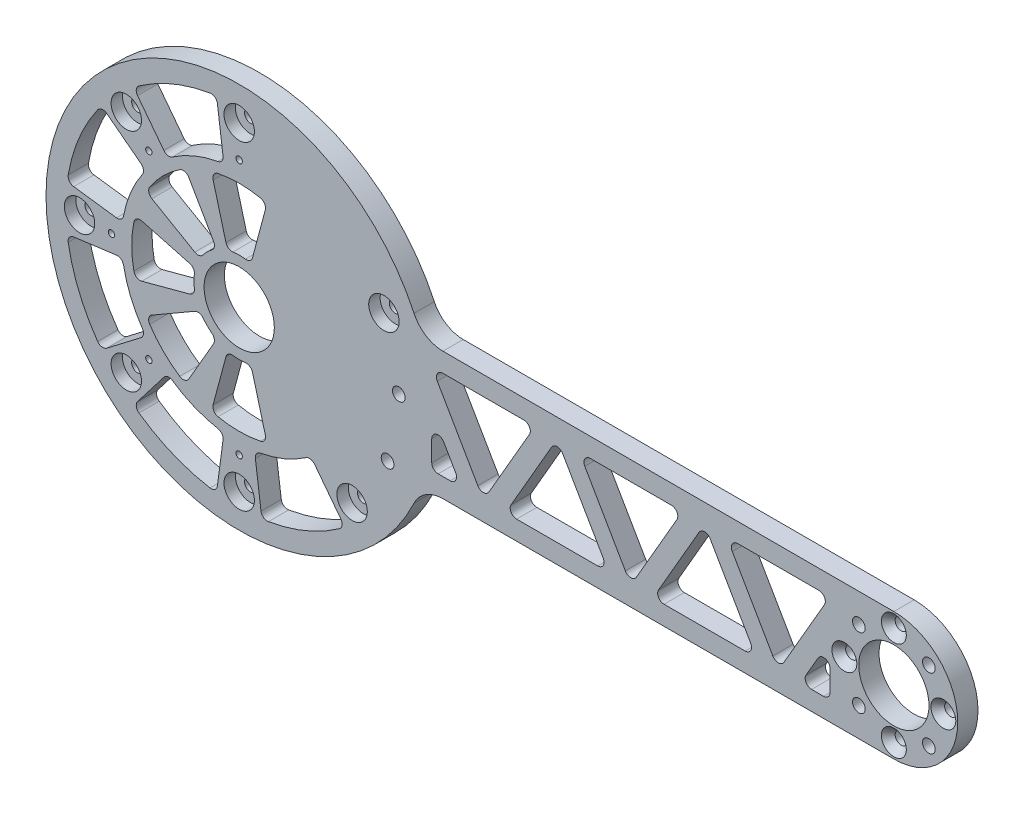
SolidWorks part; units mm, degrees
material "Balsa"
ref_plane "Front Plane" through (0, 0, 0) normal (0, 0, 1) x (1, 0, 0)
ref_plane "Top Plane" through (0, 0, 0) normal (0, 1, 0) x (1, 0, 0)
ref_plane "Right Plane" through (0, 0, 0) normal (1, 0, 0) x (0, 0, -1)
sketch "Sketch1" plane through (0, 0, 0) normal (0, 0, 1) x (1, 0, 0)
  line L0 (57.0986, -20) -> (205, -20)
  line L1 (57.0986, 20) -> (205, 20)
  line L2 (45.3154, 21.1309) -> (0, 0) construction
  line L3 (0, 0) -> (35.3553, -35.3553) construction
  line L4 (49.9788, 1.4542) -> (0, 0) construction
  line L5 (0, 0) -> (46.4674, -18.4603) construction
  arc A0 (57.0986, -20) -> (57.0986, 20) centre (0, 0) cw
  arc A1 (205, 20) -> (205, -20) centre (205, 0) cw
  circle A2 centre (0, 0) radius 60.5 construction
  circle A3 centre (0, 0) radius 11
  circle A4 centre (45.3154, 21.1309) radius 1.8986
  circle A5 centre (0, 0) radius 40 construction
  circle A6 centre (0, 0) radius 50 construction
  circle A7 centre (49.9788, 1.4542) radius 1.9939
  circle A8 centre (205, 0) radius 11
  circle A9 centre (46.4674, -18.4603) radius 1.9939
  circle A10 centre (205, 0) radius 15.5 construction
  circle A11 centre (205, -15.5) radius 1.8987
  circle A12 centre (215.9602, -10.9602) radius 1.9939
  circle A13 centre (189.5, 0) radius 1.8987
  circle A14 centre (194.0398, -10.9602) radius 1.9939
  circle A15 centre (205, 15.5) radius 1.8987
  circle A16 centre (194.0398, 10.9602) radius 1.9939
  circle A17 centre (220.5, 0) radius 1.8987
  circle A18 centre (215.9602, 10.9602) radius 1.9939
  circle A29 centre (0, -40) radius 1
  circle A30 centre (0, -50) radius 1.8986
  circle A37 centre (-28.2843, -28.2843) radius 1
  circle A38 centre (-35.3553, -35.3553) radius 1.8986
  circle A39 centre (-40, 0) radius 1
  circle A40 centre (-50, 0) radius 1.8986
  circle A41 centre (-28.2843, 28.2843) radius 1
  circle A42 centre (-35.3553, 35.3553) radius 1.8986
  circle A43 centre (0, 40) radius 1
  circle A44 centre (0, 50) radius 1.8986
  circle A45 centre (28.2843, 28.2843) radius 1 construction
  circle A46 centre (35.3553, 35.3553) radius 1.8986 construction
  circle A47 centre (40, 0) radius 1 construction
  circle A48 centre (50, 0) radius 1.8986 construction
  circle A49 centre (28.2843, -28.2843) radius 1 construction
  circle A50 centre (35.3553, -35.3553) radius 1.8986
  dimension "D1" = 121
  dimension "D4" = 22
  dimension "D6" = 100
  dimension "D7" = 80
  dimension "D8" = 70
  dimension "D9" = 3.7973
  dimension "D10" = 3.9878
  dimension "D15" = 3.7973
  dimension "D16" = 2
  dimension "D17" = 3.7973
  dimension "D18" = 3.9878
  dimension "D5" = 31
  dimension "D19" = 3.9878
  dimension "D2" = 40
  dimension "D3" = 205
  dimension "D11" = 45
  dimension "D13" = 23.333
  dimension "D14" = 23.333
  dimension "D12" = 4
  dimension "D21" = 8
extrude "Boss-Extrude1" add sketch "Sketch1" along normal blind 6.35
fillet "Fillet1" radius 10 2 edges at (57.0986, -20, 3.175) (57.0986, 20, 3.175)
sketch "Sketch2" plane through (0, 0, 6.35) normal (0, 0, 1) x (1, 0, 0)
  line L0 (60.2923, 14) -> (92.624, 14)
  line L1 (92.624, 14) -> (76.4581, -14)
  line L2 (76.4581, -14) -> (60.2923, 14)
  line L3 (83.3864, -14) -> (99.5522, 14)
  line L4 (99.5522, 14) -> (115.718, -14)
  line L5 (115.718, -14) -> (83.3864, -14)
  line L6 (106.4804, 14) -> (122.6462, -14)
  line L7 (122.6462, -14) -> (138.812, 14)
  line L8 (138.812, 14) -> (106.4804, 14)
  line L9 (129.5744, -14) -> (145.7402, 14)
  line L10 (145.7402, 14) -> (161.906, -14)
  line L11 (161.906, -14) -> (129.5744, -14)
  line L12 (152.6684, 14) -> (168.8342, -14)
  line L13 (168.8342, -14) -> (185, 14)
  line L14 (185, 14) -> (152.6684, 14)
  line L15 (60.2923, 2) -> (60.2923, -14)
  line L16 (60.2923, -14) -> (69.5299, -14)
  line L17 (69.5299, -14) -> (60.2923, 2)
  line L18 (185, 2) -> (185, -14)
  line L19 (185, -14) -> (175.7624, -14)
  line L20 (175.7624, -14) -> (185, 2)
  line L21 (205, 20) -> (63.7985, 20) construction
  line L22 (63.7985, -20) -> (205, -20) construction
  arc A0 (205, -20) -> (205, 20) centre (205, 0) ccw construction
  point P25 (225, 0)
  dimension "D1" = 60
  dimension "D2" = 60
  dimension "D3" = 6
  dimension "D4" = 6
  dimension "D5" = 6
  dimension "D6" = 6
  dimension "D7" = 6
  dimension "D8" = 6
  dimension "D9" = 6
  dimension "D10" = 6
  dimension "D11" = 40
extrude "Cut-Extrude1" cut sketch "Sketch2" against normal through all
fillet "Fillet2" radius 2 21 edges at (175.7624, -14, 3.175) (69.5299, -14, 3.175) (129.5744, -14, 3.175) (83.3864, -14, 3.175) (122.6462, -14, 3.175) (76.4581, -14, 3.175) (60.2923, -14, 3.175) (60.2923, 2, 3.175) (99.5522, 14, 3.175) (145.7402, 14, 3.175) (185, 2, 3.175) (115.718, -14, 3.175) (161.906, -14, 3.175) (185, -14, 3.175) (168.8342, -14, 3.175) (185, 14, 3.175) (138.812, 14, 3.175) (92.624, 14, 3.175) (152.6684, 14, 3.175) (106.4804, 14, 3.175) (60.2923, 14, 3.175)
other "Move Face1" [suppressed] parameters "D1"=0.08
sketch "Sketch3" plane through (0, 0, 6.35) normal (0, 0, 1) x (1, 0, 0)
  line L0 (0, 0) -> (-71.2971, 0) construction
  line L1 (-32.5034, 8.7093) -> (-13.692, 3.6688)
  line L2 (-13.692, -3.6688) -> (-32.5034, -8.7093)
  arc A0 (-13.692, -3.6688) -> (-13.692, 3.6688) centre (0, 0) cw
  arc A1 (-32.5034, -8.7093) -> (-32.5034, 8.7093) centre (0, 0) cw
  circle A2 centre (0, 0) radius 11 construction
  circle A3 centre (-40, 0) radius 1 construction
  point P7 (-14.175, 0)
  point P10 (-33.65, 0)
  dimension "D2" = 3.175
  dimension "D3" = 6.35
  dimension "D1" = 30
extrude "Cut-Extrude2" cut sketch "Sketch3" against normal through all
fillet "Fillet3" radius 2 4 edges at (-32.5034, -8.7093, 3.175) (-13.692, -3.6688, 3.175) (-13.692, 3.6688, 3.175) (-32.5034, 8.7093, 3.175)
pattern_circular "CirPattern1" count 8 over 360 about axis through (0, 0, 0) along (0, 0, 1) skipping 3, 4, 5 of "Fillet3", "Cut-Extrude2"
sketch "Sketch5" plane through (0, 0, 6.35) normal (0, 0, 1) x (1, 0, 0)
  line L0 (-78.0787, 0) -> (0, 0) construction
  line L1 (0, 0) -> (-81.1598, 33.6175) construction
  line L2 (-53.8602, 7.0908) -> (-36.51, 4.8066)
  line L3 (-43.0989, 33.071) -> (-29.2152, 22.4176)
  arc A0 (-36.51, 4.8066) -> (-29.2152, 22.4176) centre (0, 0) cw
  arc A1 (-53.8602, 7.0908) -> (-43.0989, 33.071) centre (0, 0) cw
  circle A2 centre (-35.3553, 35.3553) radius 1.8987 construction
  circle A3 centre (-28.2843, 28.2843) radius 1 construction
  circle A4 centre (-35.3553, 35.3553) radius 1.8986 construction
  circle A5 centre (-28.2843, 28.2843) radius 1 construction
  arc A6 (54.7491, 25.7447) -> (54.7491, -25.7447) centre (0, 0) ccw construction
  arc A7 (-32.9888, 6.6379) -> (-32.9888, -6.6379) centre (0, 0) ccw construction
  point P8 (-34.0219, 14.0923)
  dimension "D3" = 6.175
  dimension "D4" = 3.175
  dimension "D1" = 22.5
  dimension "D2" = 30
extrude "Cut-Extrude4" cut sketch "Sketch5" against normal through all
fillet "Fillet5" radius 2 4 edges at (-53.8602, 7.0908, 3.175) (-36.51, 4.8066, 3.175) (-29.2152, 22.4176, 3.175) (-43.0989, 33.071, 3.175)
pattern_circular "CirPattern3" count 8 over 360 about axis through (0, 0, 0) along (0, 0, 1) skipping 2, 3, 4 of "Fillet5", "Cut-Extrude4"
chamfer "Chamfer1" distance 2.301 angle 41 4 edges at (222.3986, 0, 6.35) (206.8987, -15.5, 6.35) (191.3987, 0, 6.35) (206.8987, 15.5, 6.35)
sketch "Sketch6" plane through (0, 0, 6.35) normal (0, 0, 1) x (1, 0, 0)
  circle A0 centre (45.3154, 21.1309) radius 1.8987 construction
  circle A1 centre (35.3553, -35.3553) radius 1.8987 construction
  circle A2 centre (0, -50) radius 1.8986 construction
  circle A3 centre (-35.3553, -35.3553) radius 1.8987 construction
  circle A4 centre (-50, 0) radius 1.8987 construction
  circle A5 centre (-35.3553, 35.3553) radius 1.8987 construction
  circle A6 centre (0, 50) radius 1.8986 construction
  circle A7 centre (45.3154, 21.1309) radius 1.8986
  circle A8 centre (35.3553, -35.3553) radius 1.8986
  circle A9 centre (0, -50) radius 1.8986
  circle A10 centre (-35.3553, -35.3553) radius 1.8986
  circle A11 centre (-50, 0) radius 1.8986
  circle A12 centre (-35.3553, 35.3553) radius 1.8986
  circle A13 centre (0, 50) radius 1.8986
  circle A14 centre (0, 50) radius 4.7625
  circle A15 centre (-35.3553, 35.3553) radius 4.7625
  circle A16 centre (-50, 0) radius 4.7625
  circle A17 centre (-35.3553, -35.3553) radius 4.7625
  circle A18 centre (0, -50) radius 4.7625
  circle A19 centre (35.3553, -35.3553) radius 4.7625
  circle A20 centre (45.3154, 21.1309) radius 4.7625
  dimension "D1" = 9.525
extrude "Cut-Extrude5" cut sketch "Sketch6" against normal blind 3.5719
